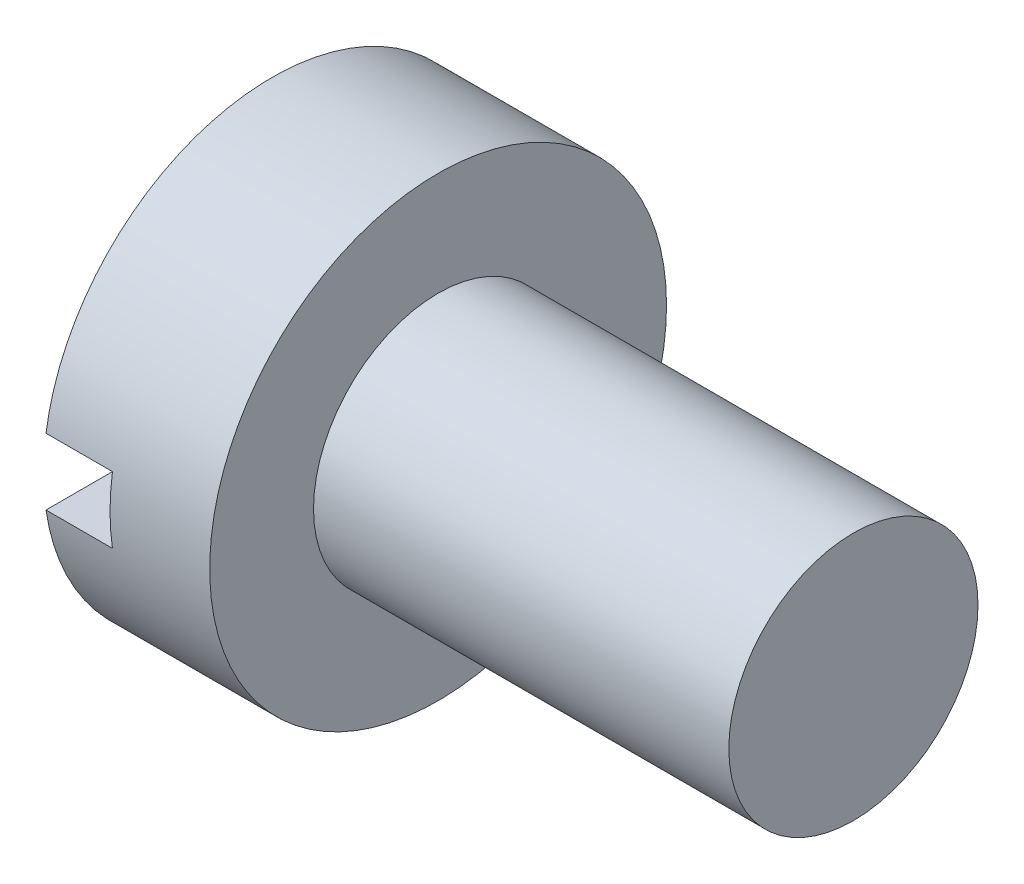
SolidWorks part; units mm, degrees
material "Plain Carbon Steel"
ref_plane "Front Plane" through (0, 0, 0) normal (0, 0, 1) x (1, 0, 0)
ref_plane "Top Plane" through (0, 0, 0) normal (0, 1, 0) x (1, 0, 0)
ref_plane "Right Plane" through (0, 0, 0) normal (1, 0, 0) x (0, 0, -1)
sketch "Sketch1" plane through (0, 0, 0) normal (0, 0, 1) x (1, 0, 0)
  line L0 (0, 0) -> (0, 2.75)
  line L1 (0, 2.75) -> (2, 2.75)
  line L2 (2, 2.75) -> (2, 1.5)
  line L3 (2, 1.5) -> (7, 1.5)
  line L4 (7, 1.5) -> (7, 0)
  line L5 (7, 0) -> (0, 0) construction
  line L6 (0, 0) -> (7, 0)
  dimension "D1" = 3
  dimension "D2" = 5
  dimension "D3" = 5.5
  dimension "D4" = 2
revolve "Revolve1" add sketch "Sketch1" angle 360 about L5
sketch "Sketch2" plane through (0, 0, 0) normal (-1, 0, 0) x (0, 0, 1)
  line L0 (2.75, 0) -> (-2.75, 0) construction
  line L1 (-2.75, 0.4) -> (2.75, 0.4)
  line L2 (-2.75, 0.4) -> (-2.75, -0.4)
  line L3 (-2.75, -0.4) -> (2.75, -0.4)
  line L4 (2.75, 0.4) -> (2.75, -0.4)
  circle A0 centre (0, 0) radius 2.75 construction
  dimension "D1" = 0.8
extrude "Cut-Extrude1" cut sketch "Sketch2" against normal blind 0.8
